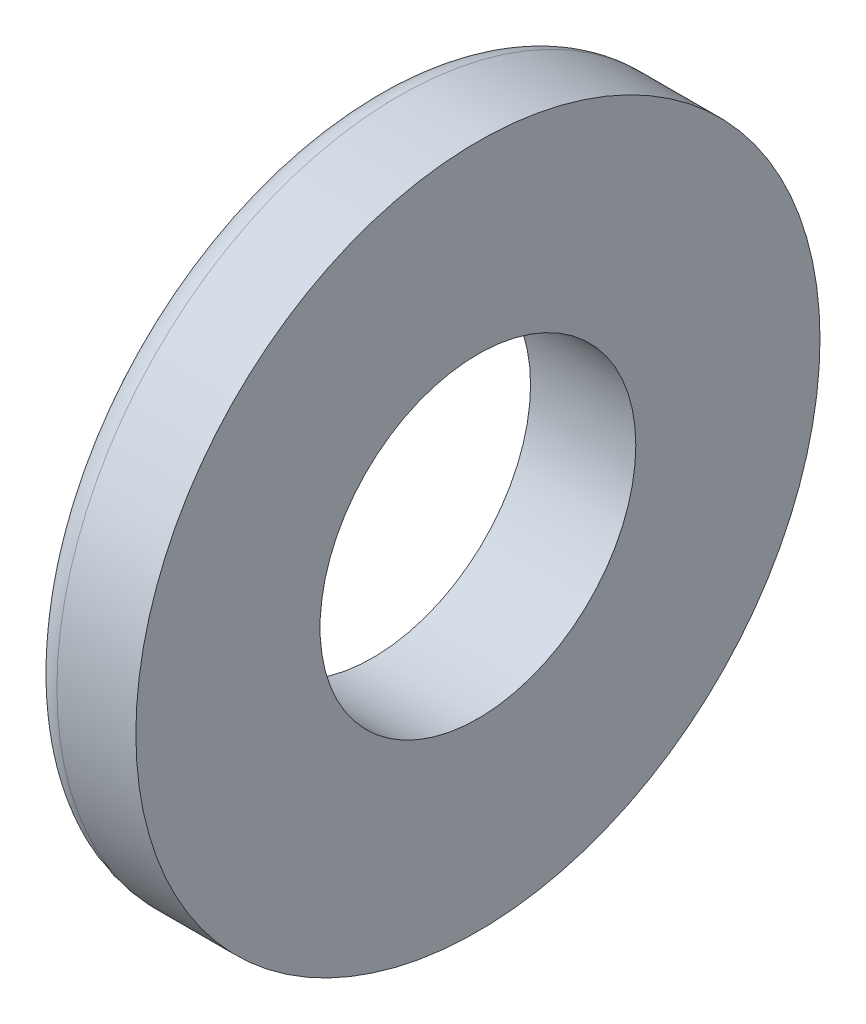
SolidWorks part; units mm, degrees
ref_plane "Front Plane" through (0, 0, 0) normal (0, 0, 1) x (1, 0, 0)
ref_plane "Top Plane" through (0, 0, 0) normal (0, 1, 0) x (1, 0, 0)
ref_plane "Right Plane" through (0, 0, 0) normal (1, 0, 0) x (0, 0, -1)
sketch "Sketch2" plane through (0, 0, 0) normal (1, 0, 0) x (0, 0, -1)
  circle A0 centre (0, 0) radius 3
  circle A2 centre (0, 0) radius 6.5
  dimension "D1" = 6
  dimension "D2" = 13
extrude "Boss-Extrude1" add sketch "Sketch2" along normal blind 2
fillet "Fillet1" radius 0.5 1 edges at (0, 0, -6.5)
